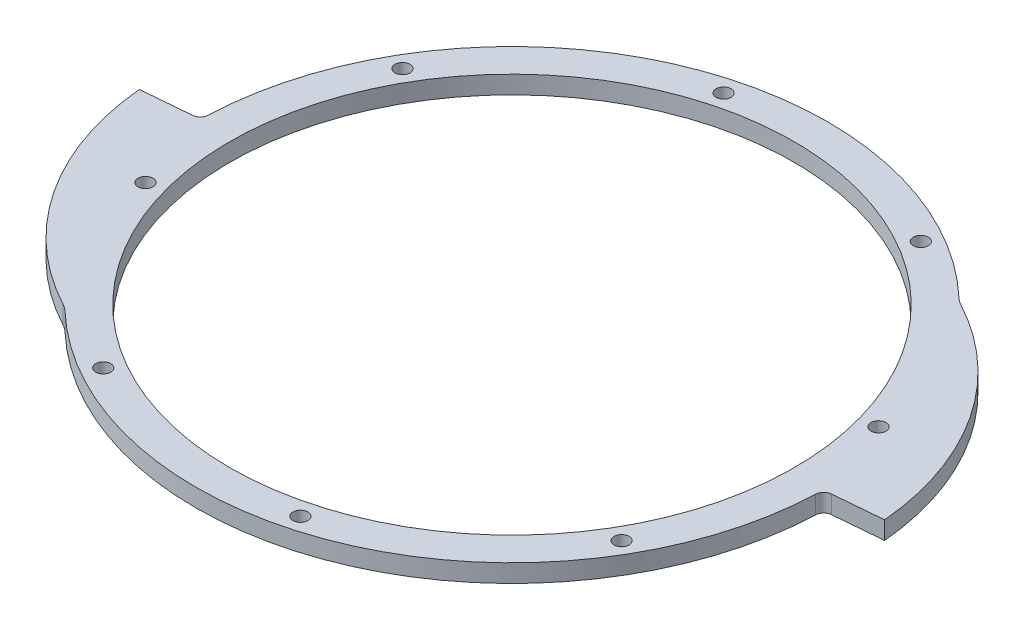
SolidWorks part; units mm, degrees
material "Alloy Steel"
ref_plane "Front Plane" through (0, 0, 0) normal (0, 0, 1) x (1, 0, 0)
ref_plane "Top Plane" through (0, 0, 0) normal (0, 1, 0) x (1, 0, 0)
ref_plane "Right Plane" through (0, 0, 0) normal (1, 0, 0) x (0, 0, -1)
sketch "Sketch1" plane through (0, 0, 0) normal (0, 1, 0) x (1, 0, 0)
  line L0 (0, 0) -> (-132, 0) construction
  line L1 (-132.0082, 0.0941) -> (-134.7743, 31.7103) construction
  line L2 (-111.9863, 1.751) -> (-132, 0)
  line L3 (-132, 0) -> (-132, 32.0934) construction
  line L4 (-129.3938, 0) -> (-182.8754, 0) construction
  line L5 (-112, 0) -> (-132, 0) construction
  line L6 (-79.4774, -79.4774) -> (0, 0) construction
  circle A0 centre (0, 0) radius 100
  arc A10 (-132, 0) -> (-79.4774, -79.4774) centre (-32.4231, 8.7118) ccw
  arc A11 (-79.4774, -79.4774) -> (-77.2845, -81.0624) centre (-84.1849, -88.3001) cw
  arc A12 (-77.2845, -81.0624) -> (-111.9863, 1.751) centre (0, 0) ccw
  dimension "D1" = 200
  dimension "D6" = 10
  dimension "D4" = 5
  dimension "D7" = 45
  dimension "D2" = 12
  dimension "D3" = 5
  dimension "D5" = 20
extrude "Boss-Extrude1" add sketch "Sketch1" along normal mid plane 6.35
fillet "Fillet1" radius 3 1 edges at (-111.9863, 0, -1.751)
pattern_circular "CirPattern1" count 2 over 360 about axis through (0, 0, 0) along (0, 1, 0) of "Boss-Extrude1", "Fillet1"
sketch "Sketch2" plane through (0, 3.175, 0) normal (0, 1, 0) x (1, 0, 0)
  line L0 (-102.3881, -27.4348) -> (0, 0) construction
  line L1 (0, 0) -> (-106, 0) construction
  circle A0 centre (-102.3881, -27.4348) radius 2.65
  circle A2 centre (0, 0) radius 106 construction
  circle A3 centre (0, 0) radius 100 construction
  dimension "D3" = 5.3
  dimension "D1" = 106
  dimension "D2" = 6
  dimension "D4" = 15
extrude "Cut-Extrude1" cut sketch "Sketch2" against normal through all
pattern_circular "CirPattern2" count 8 over 360 about axis through (0, 0, 0) along (0, 1, 0) of "Cut-Extrude1"
equation "\"ring_id\"=200"
equation "\"D1@Sketch1\"=\"ring_id\""
equation "\"D2@Sketch2\"=\"D2@Sketch1\"/2"
